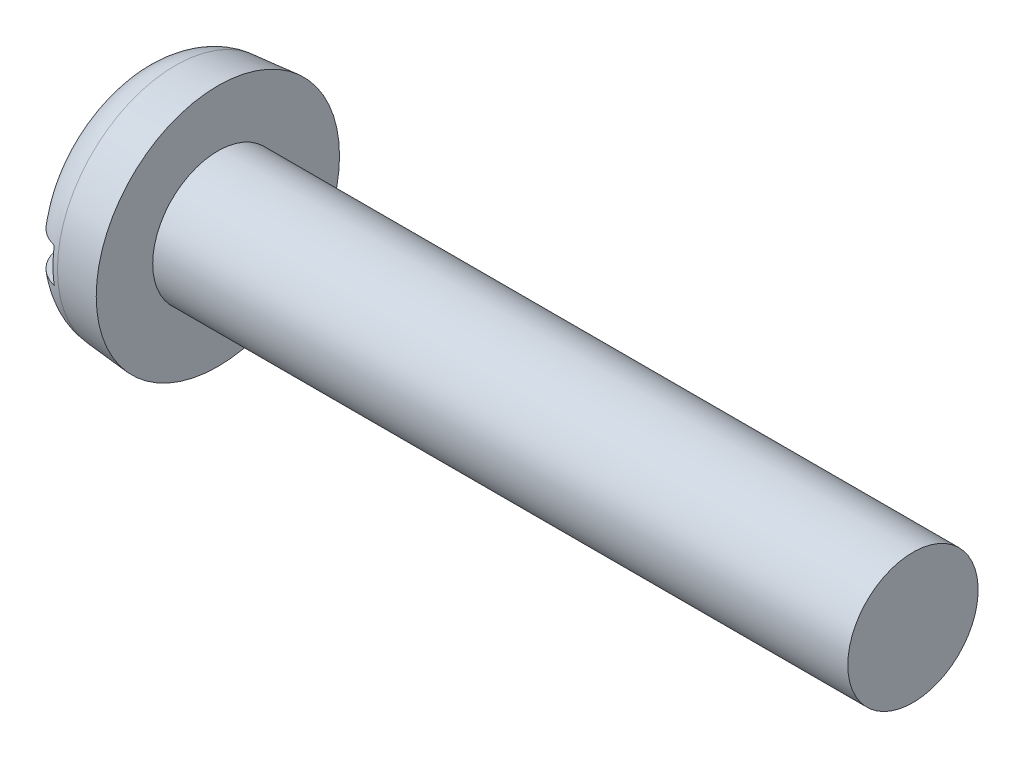
SolidWorks part; units mm, degrees
ref_plane "Plane1" through (0, 0, 0) normal (0, 0, 1) x (1, 0, 0)
ref_plane "Plane2" through (0, 0, 0) normal (0, 1, 0) x (1, 0, 0)
ref_plane "Plane3" through (0, 0, 0) normal (1, 0, 0) x (0, 0, -1)
sketch "BodySke" plane through (0, 0, 0) normal (0, 0, 1) x (1, 0, 0)
  line L0 (1.8, 1.5) -> (1.8, 2.8)
  line L1 (0, 0) -> (0, 2.6425)
  line L2 (-25.4, 0) -> (127, 0) construction
  line L3 (17.8, 0) -> (0, 0)
  line L4 (1.8, 1.5) -> (17.8, 1.5)
  line L5 (17.8, 1.5) -> (17.8, 0)
  line L6 (0, 2.6425) -> (1.8, 2.8)
  line L9 (2.3, 3.0875) -> (2.3, -6.4375) construction
  line L10 (1.8, 6.35) -> (1.8, -3.175) construction
  dimension "Length" = 16
  dimension "Head_ht" = 1.8
  dimension "Advance" = 0.5
  dimension "Thread_nom" = 16
  dimension "Head_dia" = 5.6
  dimension "Head_side_angle" = 5
  dimension "Diameter" = 3
revolve "Base-Revolve" add sketch "BodySke"
cosmetic thread "ThreadCosmetic" [suppressed]
fillet "Fillet1" [suppressed] radius 0.1
fillet "Fillet2" radius 0.9 1 edges at (0, 0, 2.6425)
sketch "Sketch2" plane through (0, 0, 0) normal (1, 0, 0) x (0, 0, -1)
  line L0 (2.8, -0.4) -> (-2.8, -0.4)
  line L1 (2.8, -0.4) -> (2.8, 0.4)
  line L2 (-2.8, 0.4) -> (2.8, 0.4)
  line L3 (-2.8, 0.4) -> (-2.8, -0.4)
  dimension "D1" = 5.6
  dimension "Slot_width" = 0.8
  dimension "D2" = 2.8
  dimension "D3" = 0.4
extrude "Slot" cut sketch "Sketch2" along normal blind 0.7
sketch "ThdSchSke" plane through (0, 0, 0) normal (0, 0, 1) x (1, 0, 0)
  line L0 (2.8, -1.2195) -> (2.6036, -1.5)
  line L1 (2.8, -1.2195) -> (2.9964, -1.5)
  line L2 (2.9964, -1.5) -> (2.9964, -1.875)
  line L3 (-3.175, 0) -> (5.1513, 0) construction
  line L5 (2.9964, -1.875) -> (2.6036, -1.875)
  line L6 (2.6036, -1.875) -> (2.6036, -1.5)
  dimension "Diameter" = 3
  dimension "SideAngle" = 55
  dimension "VeeAngle" = 70
  dimension "Thread_minor" = 2.439
  dimension "Overcut" = 3.75
  dimension "Start" = 2.8
revolve "ThreadSchematic" [suppressed] cut sketch "ThdSchSke" angle 360 about L3
pattern_linear "ThdSchPat" [suppressed]
equation "\"D1@Sketch2\" = \"Head_dia@BodySke\""
equation "\"D2@Sketch2\" = \"D1@Sketch2\" / 2"
equation "\"D3@Sketch2\" = \"Slot_width@Sketch2\" / 2"
equation "\"Thread_length@ThreadCosmetic\" = ((sgn( (\"Length@BodySke\" - \"Advance@BodySke\" * 2.0 ) - \"Thread_nom@BodySke\" )-1)*( (\"Length@BodySke\" - \"Advance@BodySke\"  * 2.0) - \"Thread_nom@BodySke\" ))/-2+ \"Thread_nom@BodySke\""
equation "\"Thread_minor@ThdSchSke\" = \"Thread_minor@ThreadCosmetic\""
equation "\"Diameter@ThdSchSke\" = \"Diameter@BodySke\""
equation "\"Overcut@ThdSchSke\" = \"Diameter@BodySke\" * 1.25"
equation "\"Start@ThdSchSke\" = \"Head_ht@BodySke\" + \"Length@BodySke\" - \"Thread_length@ThreadCosmetic\"  '---Non-countersunk---"
equation "\"Num_threads@ThdSchPat\" = int( \"Thread_length@ThreadCosmetic\" / \"Advance@BodySke\" + 0.999 )  + 1"
equation "\"Advance@ThdSchPat\" = \"Thread_length@ThreadCosmetic\" /  (\"Num_threads@ThdSchPat\" - 1) 'relax it"
